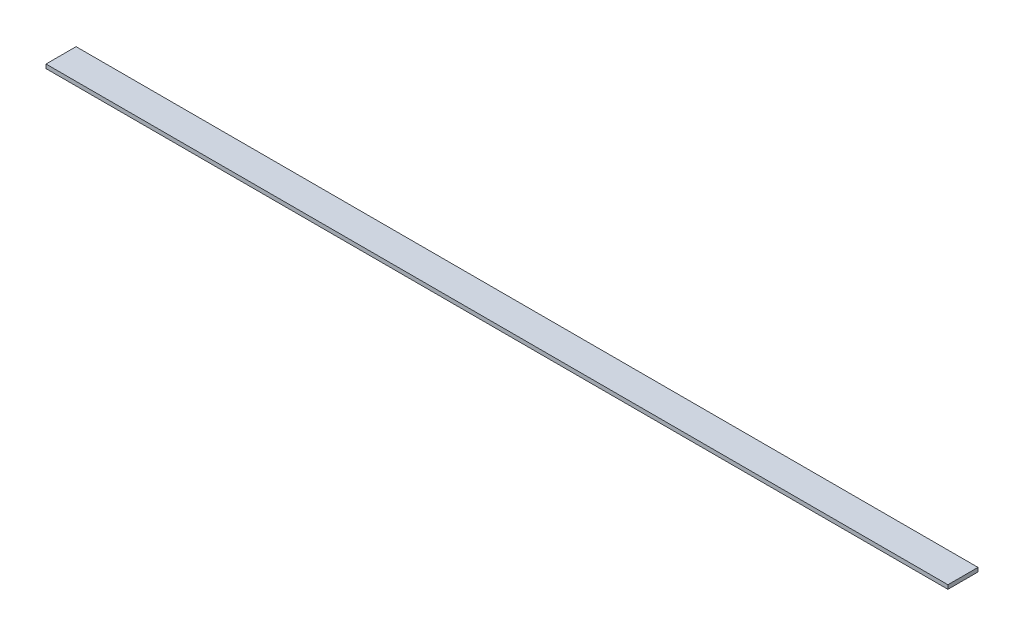
SolidWorks part; units mm, degrees
ref_plane "前视基准面" through (0, 0, 0) normal (0, 0, 1) x (1, 0, 0)
ref_plane "上视基准面" through (0, 0, 0) normal (0, 1, 0) x (1, 0, 0)
ref_plane "右视基准面" through (0, 0, 0) normal (1, 0, 0) x (0, 0, -1)
sketch "草图1" plane through (0, 0, 0) normal (0, 1, 0) x (1, 0, 0)
  line L1 (-2250, 75) -> (2250, 75)
  line L2 (-2250, 75) -> (-2250, -75)
  line L3 (-2250, -75) -> (2250, -75)
  line L4 (2250, 75) -> (2250, -75)
  line L5 (-2250, 75) -> (2250, -75) construction
  line L6 (-2250, -75) -> (2250, 75) construction
  line L24 (0, -75) -> (0, 75) construction
  line L25 (2250, 0) -> (-2250, 0) construction
extrude "凸台-拉伸1" add sketch "草图1" along normal blind 20
sketch "草图3" plane through (0, 20, 0) normal (0, 1, 0) x (1, 0, 0)
  line L0 (0, 75) -> (0, -75)
  line L1 (-79, 64) -> (-71, 64)
  line L2 (-79, 64) -> (-79, -64)
  line L3 (-79, -64) -> (-71, -64)
  line L4 (-71, 64) -> (-71, -64)
  line L5 (-79, 64) -> (-71, -64) construction
  line L6 (-79, -64) -> (-71, 64) construction
  line L7 (2250, 75) -> (-2250, 75) construction
  line L8 (-229, 64) -> (-221, 64)
  line L9 (-229, 64) -> (-229, -64)
  line L10 (-229, -64) -> (-221, -64)
  line L11 (-221, 64) -> (-221, -64)
  line L12 (-229, 64) -> (-221, -64) construction
  line L13 (-229, -64) -> (-221, 64) construction
  line L14 (-379, 64) -> (-371, 64)
  line L15 (-379, 64) -> (-379, -64)
  line L16 (-379, -64) -> (-371, -64)
  line L17 (-371, 64) -> (-371, -64)
  line L18 (-379, 64) -> (-371, -64) construction
  line L19 (-379, -64) -> (-371, 64) construction
  line L20 (-529, 64) -> (-521, 64)
  line L21 (-529, 64) -> (-529, -64)
  line L22 (-529, -64) -> (-521, -64)
  line L23 (-521, 64) -> (-521, -64)
  line L24 (-529, 64) -> (-521, -64) construction
  line L25 (-529, -64) -> (-521, 64) construction
  line L26 (-679, 64) -> (-671, 64)
  line L27 (-679, 64) -> (-679, -64)
  line L28 (-679, -64) -> (-671, -64)
  line L29 (-671, 64) -> (-671, -64)
  line L30 (-679, 64) -> (-671, -64) construction
  line L31 (-679, -64) -> (-671, 64) construction
  line L32 (-829, 64) -> (-821, 64)
  line L33 (-829, 64) -> (-829, -64)
  line L34 (-829, -64) -> (-821, -64)
  line L35 (-821, 64) -> (-821, -64)
  line L36 (-829, 64) -> (-821, -64) construction
  line L37 (-829, -64) -> (-821, 64) construction
  line L38 (-829, 64) -> (-821, 64)
  line L39 (-829, 64) -> (-829, -64)
  line L40 (-829, -64) -> (-821, -64)
  line L41 (-821, 64) -> (-821, -64)
  line L42 (-829, 64) -> (-821, -64) construction
  line L43 (-829, -64) -> (-821, 64) construction
  line L44 (-979, 64) -> (-971, 64)
  line L45 (-979, 64) -> (-979, -64)
  line L46 (-979, -64) -> (-971, -64)
  line L47 (-971, 64) -> (-971, -64)
  line L48 (-979, 64) -> (-971, -64) construction
  line L49 (-979, -64) -> (-971, 64) construction
  line L50 (-1129, 64) -> (-1121, 64)
  line L51 (-1129, 64) -> (-1129, -64)
  line L52 (-1129, -64) -> (-1121, -64)
  line L53 (-1121, 64) -> (-1121, -64)
  line L54 (-1129, 64) -> (-1121, -64) construction
  line L55 (-1129, -64) -> (-1121, 64) construction
  line L56 (-1279, 64) -> (-1271, 64)
  line L57 (-1279, 64) -> (-1279, -64)
  line L58 (-1279, -64) -> (-1271, -64)
  line L59 (-1271, 64) -> (-1271, -64)
  line L60 (-1279, 64) -> (-1271, -64) construction
  line L61 (-1279, -64) -> (-1271, 64) construction
  line L62 (-1429, 64) -> (-1421, 64)
  line L63 (-1429, 64) -> (-1429, -64)
  line L64 (-1429, -64) -> (-1421, -64)
  line L65 (-1421, 64) -> (-1421, -64)
  line L66 (-1429, 64) -> (-1421, -64) construction
  line L67 (-1429, -64) -> (-1421, 64) construction
  line L68 (-1579, 64) -> (-1571, 64)
  line L69 (-1579, 64) -> (-1579, -64)
  line L70 (-1579, -64) -> (-1571, -64)
  line L71 (-1571, 64) -> (-1571, -64)
  line L72 (-1579, 64) -> (-1571, -64) construction
  line L73 (-1579, -64) -> (-1571, 64) construction
  line L74 (-1879, 64) -> (-1871, 64)
  line L75 (-1879, 64) -> (-1879, -64)
  line L76 (-1879, -64) -> (-1871, -64)
  line L77 (-1871, 64) -> (-1871, -64)
  line L78 (-1879, 64) -> (-1871, -64) construction
  line L79 (-1879, -64) -> (-1871, 64) construction
  line L80 (-2250, -75) -> (2250, -75) construction
  line L81 (71, 64) -> (79, 64)
  line L82 (71, 64) -> (71, -64)
  line L83 (71, -64) -> (79, -64)
  line L84 (79, 64) -> (79, -64)
  line L85 (71, 64) -> (79, -64) construction
  line L86 (-1729, 64) -> (-1721, 64)
  line L87 (-1729, 64) -> (-1729, -64)
  line L88 (-1729, -64) -> (-1721, -64)
  line L89 (-1721, 64) -> (-1721, -64)
  line L90 (-1729, 64) -> (-1721, -64) construction
  line L91 (-1729, -64) -> (-1721, 64) construction
  line L92 (-2029, 64) -> (-2021, 64)
  line L93 (-2029, 64) -> (-2029, -64)
  line L94 (-2029, -64) -> (-2021, -64)
  line L95 (-2021, 64) -> (-2021, -64)
  line L96 (-2029, 64) -> (-2021, -64) construction
  line L97 (-2029, -64) -> (-2021, 64) construction
  line L98 (71, -64) -> (79, 64) construction
  line L99 (221, 64) -> (229, 64)
  line L100 (221, 64) -> (221, -64)
  line L101 (221, -64) -> (229, -64)
  line L102 (229, 64) -> (229, -64)
  line L103 (221, 64) -> (229, -64) construction
  line L104 (221, -64) -> (229, 64) construction
  line L105 (371, 64) -> (379, 64)
  line L106 (371, 64) -> (371, -64)
  line L107 (371, -64) -> (379, -64)
  line L108 (379, 64) -> (379, -64)
  line L109 (371, 64) -> (379, -64) construction
  line L110 (371, -64) -> (379, 64) construction
  line L111 (521, 64) -> (529, 64)
  line L112 (521, 64) -> (521, -64)
  line L113 (521, -64) -> (529, -64)
  line L114 (529, 64) -> (529, -64)
  line L115 (521, 64) -> (529, -64) construction
  line L116 (521, -64) -> (529, 64) construction
  line L117 (671, 64) -> (679, 64)
  line L118 (671, 64) -> (671, -64)
  line L119 (671, -64) -> (679, -64)
  line L120 (679, 64) -> (679, -64)
  line L121 (671, 64) -> (679, -64) construction
  line L122 (671, -64) -> (679, 64) construction
  line L123 (821, 64) -> (829, 64)
  line L124 (821, 64) -> (821, -64)
  line L125 (821, -64) -> (829, -64)
  line L126 (829, 64) -> (829, -64)
  line L127 (821, 64) -> (829, -64) construction
  line L128 (821, -64) -> (829, 64) construction
  line L129 (971, 64) -> (979, 64)
  line L130 (971, 64) -> (971, -64)
  line L131 (971, -64) -> (979, -64)
  line L132 (979, 64) -> (979, -64)
  line L133 (971, 64) -> (979, -64) construction
  line L134 (971, -64) -> (979, 64) construction
  line L135 (1121, 64) -> (1129, 64)
  line L136 (1121, 64) -> (1121, -64)
  line L137 (1121, -64) -> (1129, -64)
  line L138 (1129, 64) -> (1129, -64)
  line L139 (1121, 64) -> (1129, -64) construction
  line L140 (1121, -64) -> (1129, 64) construction
  line L141 (1271, 64) -> (1279, 64)
  line L142 (1271, 64) -> (1271, -64)
  line L143 (1271, -64) -> (1279, -64)
  line L144 (1279, 64) -> (1279, -64)
  line L145 (1271, 64) -> (1279, -64) construction
  line L146 (1271, -64) -> (1279, 64) construction
  line L147 (1421, 64) -> (1429, 64)
  line L148 (1421, 64) -> (1421, -64)
  line L149 (1421, -64) -> (1429, -64)
  line L150 (1429, 64) -> (1429, -64)
  line L151 (1421, 64) -> (1429, -64) construction
  line L152 (1421, -64) -> (1429, 64) construction
  line L153 (1721, 64) -> (1729, 64)
  line L154 (1721, 64) -> (1721, -64)
  line L155 (1721, -64) -> (1729, -64)
  line L156 (1729, 64) -> (1729, -64)
  line L157 (1721, 64) -> (1729, -64) construction
  line L158 (1721, -64) -> (1729, 64) construction
  line L159 (1571, 64) -> (1579, 64)
  line L160 (1571, 64) -> (1571, -64)
  line L161 (1571, -64) -> (1579, -64)
  line L162 (1579, 64) -> (1579, -64)
  line L163 (1571, 64) -> (1579, -64) construction
  line L164 (1571, -64) -> (1579, 64) construction
  line L165 (1871, 64) -> (1879, 64)
  line L166 (1871, 64) -> (1871, -64)
  line L167 (1871, -64) -> (1879, -64)
  line L168 (1879, 64) -> (1879, -64)
  line L169 (1871, 64) -> (1879, -64) construction
  line L170 (1871, -64) -> (1879, 64) construction
  line L171 (2021, 64) -> (2029, 64)
  line L172 (2021, 64) -> (2021, -64)
  line L173 (2021, -64) -> (2029, -64)
  line L174 (2029, 64) -> (2029, -64)
  line L175 (2021, 64) -> (2029, -64) construction
  line L176 (2021, -64) -> (2029, 64) construction
  point P0 (-75, 0)
  point P7 (-225, 0)
  point P12 (-375, 0)
  point P17 (-525, 0)
  point P22 (-675, 0)
  point P27 (-825, 0)
  point P32 (-825, 0)
  point P37 (-975, 0)
  point P42 (-1125, 0)
  point P47 (-1275, 0)
  point P52 (-1425, 0)
  point P57 (-1575, 0)
  point P62 (-1875, 0)
  point P71 (75, 0)
  point P72 (-1725, 0)
  point P77 (-2025, 0)
  point P86 (225, 0)
  point P91 (375, 0)
  point P96 (525, 0)
  point P101 (675, 0)
  point P106 (825, 0)
  point P111 (975, 0)
  point P116 (1125, 0)
  point P121 (1275, 0)
  point P126 (1425, 0)
  point P131 (1725, 0)
  point P136 (1575, 0)
  point P141 (1875, 0)
  point P146 (2025, 0)
